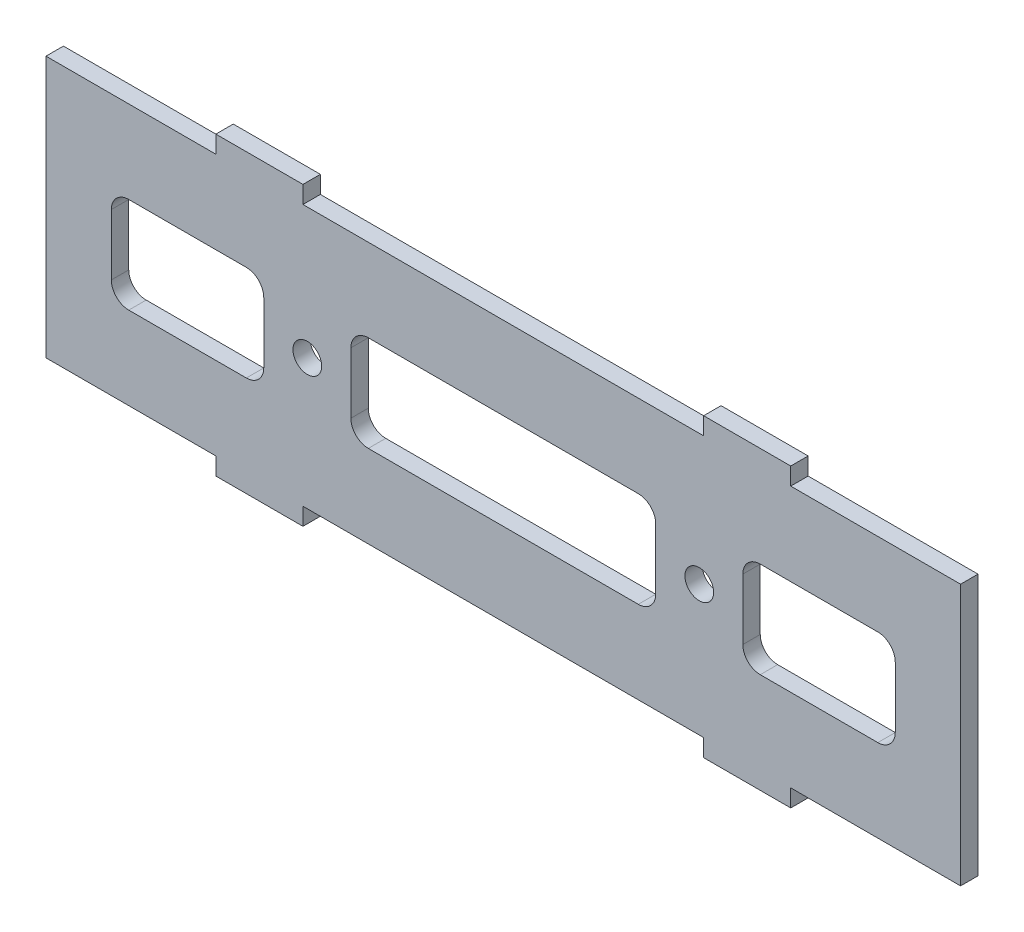
SolidWorks part; units mm, degrees
ref_plane "前视基准面" through (0, 0, 0) normal (0, 0, 1) x (1, 0, 0)
ref_plane "上视基准面" through (0, 0, 0) normal (0, 1, 0) x (1, 0, 0)
ref_plane "右视基准面" through (0, 0, 0) normal (1, 0, 0) x (0, 0, -1)
sketch "草图1" plane through (0, 0, 0) normal (0, 0, 1) x (1, 0, 0)
  line L0 (-33, -15) -> (-52.5, -15)
  line L1 (52.5, -15) -> (33, -15)
  line L2 (52.5, -15) -> (52.5, 15)
  line L3 (52.5, 15) -> (33, 15)
  line L4 (-52.5, -15) -> (-52.5, 15)
  line L5 (52.5, -15) -> (-52.5, 15) construction
  line L6 (52.5, 15) -> (-52.5, -15) construction
  line L8 (-33, -15) -> (-33, -17)
  line L9 (-33, -17) -> (-23, -17)
  line L10 (-23, -15) -> (-23, -17)
  line L12 (23, -15) -> (23, -17)
  line L13 (23, -17) -> (33, -17)
  line L14 (33, -15) -> (33, -17)
  line L15 (23, -15) -> (-23, -15)
  line L16 (-33, 15) -> (-52.5, 15)
  line L18 (-33, 15) -> (-33, 17)
  line L19 (-33, 17) -> (-23, 17)
  line L20 (-23, 15) -> (-23, 17)
  line L22 (23, 15) -> (23, 17)
  line L23 (23, 17) -> (33, 17)
  line L24 (33, 15) -> (33, 17)
  line L25 (23, 15) -> (-23, 15)
  point P0 (0, 0)
  dimension "D1" = 30
  dimension "D2" = 105
  dimension "D3" = 2
  dimension "D4" = 10
  dimension "D5" = 2
  dimension "D6" = 10
  dimension "D7" = 46
  dimension "D8" = 23
  dimension "D9" = 2
  dimension "D10" = 10
  dimension "D11" = 2
  dimension "D12" = 10
extrude "凸台-拉伸1" add sketch "草图1" along normal blind 2
sketch "草图2" plane through (0, 0, 2) normal (0, 0, 1) x (1, 0, 0)
  line L0 (-52.5, -10) -> (52.5, -10) construction
  line L1 (-52.5, 15) -> (-52.5, -15) construction
  line L2 (52.5, -15) -> (52.5, 15) construction
  line L3 (-23, -15) -> (23, -15) construction
  line L5 (45, -5.5) -> (-45, -5.5)
  line L6 (45, -5.5) -> (45, 5.5)
  line L7 (45, 5.5) -> (-45, 5.5)
  line L8 (-45, -5.5) -> (-45, 5.5)
  line L9 (45, -5.5) -> (-45, 5.5) construction
  line L10 (45, 5.5) -> (-45, -5.5) construction
  point P8 (0, 0)
  dimension "D1" = 5
  dimension "D2" = 11
  dimension "D3" = 90
extrude "切除-拉伸1" cut sketch "草图2" against normal blind 2
sketch "草图4" plane through (0, 0, 0) normal (0, 0, -1) x (-1, 0, 0)
  line L0 (-33, -15) -> (-52.5, -15) construction
  line L1 (23, -15) -> (-23, -15) construction
  line L3 (-17.5, -5.5) -> (-27.5, -5.5)
  line L4 (-17.5, -5.5) -> (-17.5, 5.5)
  line L5 (-17.5, 5.5) -> (-27.5, 5.5)
  line L6 (-27.5, -5.5) -> (-27.5, 5.5)
  line L7 (-17.5, -5.5) -> (-27.5, 5.5) construction
  line L8 (-17.5, 5.5) -> (-27.5, -5.5) construction
  line L9 (-45, 5.5) -> (45, 5.5) construction
  line L11 (27.5, -5.5) -> (17.5, -5.5)
  line L12 (27.5, -5.5) -> (27.5, 5.5)
  line L13 (27.5, 5.5) -> (17.5, 5.5)
  line L14 (17.5, -5.5) -> (17.5, 5.5)
  line L15 (27.5, -5.5) -> (17.5, 5.5) construction
  line L16 (27.5, 5.5) -> (17.5, -5.5) construction
  circle A0 centre (-22.5, 0) radius 1.65
  circle A1 centre (22.5, 0) radius 1.65
  dimension "D1" = 3.3
  dimension "D2" = 3.3
  dimension "D3" = 3.3
  dimension "D4" = 15
  dimension "D5" = 22.5
  dimension "D6" = 22.5
  dimension "D7" = 15
  dimension "D9" = 10
  dimension "D11" = 10
extrude "凸台-拉伸3" add sketch "草图4" against normal up to surface (2 mm away) up to face at (0, 0, 2)
fillet "圆角2" radius 2 12 edges at (45, -5.5, 1) (45, 5.5, 1) (27.5, 5.5, 1) (27.5, -5.5, 1) (17.5, -5.5, 1) (17.5, 5.5, 1) (-17.5, -5.5, 1) (-17.5, 5.5, 1) (-27.5, -5.5, 1) (-45, -5.5, 1) (-45, 5.5, 1) (-27.5, 5.5, 1)
